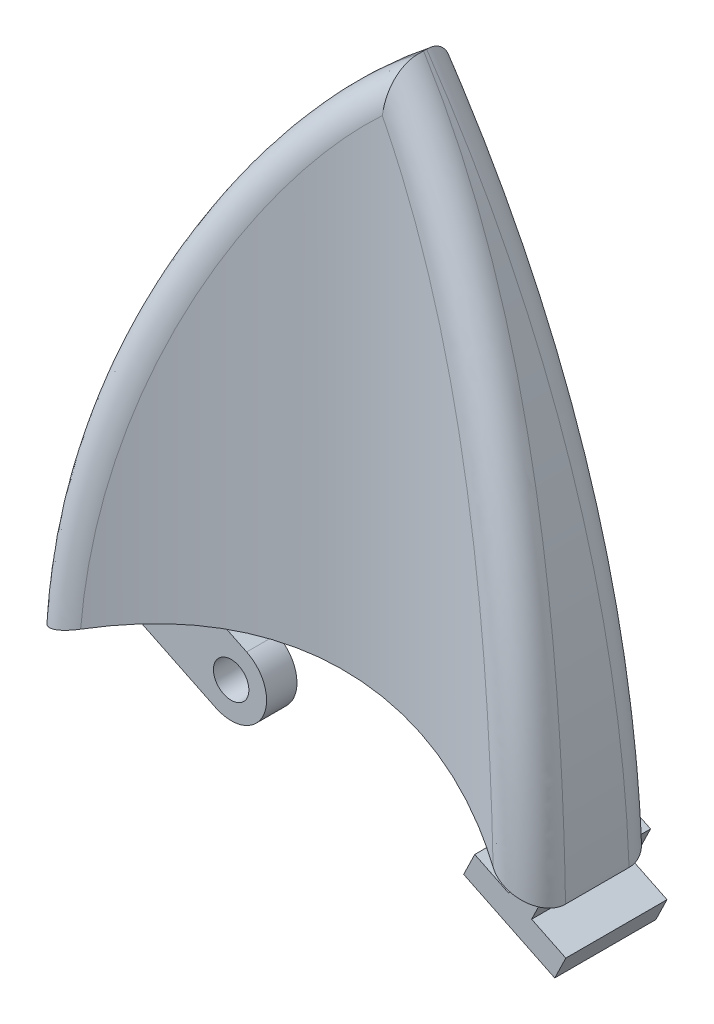
SolidWorks part; units mm, degrees
ref_plane "Plano frontal" through (0, 0, 0) normal (0, 0, 1) x (1, 0, 0)
ref_plane "Plano superior" through (0, 0, 0) normal (0, 1, 0) x (1, 0, 0)
ref_plane "Plano direito" through (0, 0, 0) normal (1, 0, 0) x (0, 0, -1)
sketch "Esboço6" plane through (0, 0, 0) normal (0, 0, 1) x (1, 0, 0)
  line L0 (0, 0) -> (0, 60.7591) construction
  line L1 (-45.3755, 22.0332) -> (30.2231, -14.6756) construction
  line L2 (20.4812, 42.1794) -> (-17.5967, -36.239) construction
  dimension "D1" = 64.1
sketch "Esboço1" plane through (0, 0, 0) normal (0, 1, 0) x (1, 0, 0)
  line L1 (-25, 0) -> (25, 0)
  line L2 (-25, 0) -> (-25, -15)
  line L3 (-25, -15) -> (25, -15)
  line L4 (25, 0) -> (25, -15)
  dimension "D2" = 15
  dimension "D1" = 50
extrude "Ressalto-extrusão1" add sketch "Esboço1" along normal blind 60
sketch "Esboço2" plane through (0, 0, 0) normal (0, 0, 1) x (1, 0, 0)
  line L1 (5, 60) -> (25, 60)
  line L2 (25, 60) -> (25, 0)
  line L4 (-25, 0) -> (25, 0) construction
  arc A0 (5, 60) -> (25, 0) centre (-88.2934, -4.4311) cw
  dimension "D1" = 20
  dimension "D2" = 113.38
extrude "Corte-extrusão1" cut sketch "Esboço2" along normal up to next and the other way through all
sketch "Esboço3" plane through (0, 0, 0) normal (0, 0, -1) x (-1, 0, 0)
  line L0 (-5, 60) -> (25, 60)
  line L1 (25, 60) -> (25, 0)
  line L2 (25, 0) -> (-25, 0) construction
  line L3 (25, 60) -> (25, 0) construction
  arc A0 (25, 0) -> (-5, 60) centre (-54.9615, -2.4808) ccw
  dimension "D1" = 80
extrude "Corte-extrusão2" cut sketch "Esboço3" against normal up to next
sketch "Esboço4" plane through (0, 0, 0) normal (0, -1, 0) x (1, 0, 0)
  line L0 (-25, 15) -> (25, 15) construction
  line L1 (-25, 0) -> (-25, 15) construction
  line L2 (-25, 15) -> (25, 15)
  arc A0 (-25, 15) -> (25, 15) centre (0, 46.225) ccw
  point P3 (0, 6.225)
  dimension "D1" = 40
extrude "Corte-extrusão3" cut sketch "Esboço4" against normal blind 60
fillet "Filete1" radius 3 4 edges at (19.2683, 31.4228, 0) (19.2315, 31.5331, 11.1515) (-16.5926, 33.2963, 0) (-12.5703, 40.408, 8.2515)
sketch "Esboço5" plane through (0, 0, 0) normal (0, 0, 1) x (1, 0, 0)
  line L0 (-25, 0) -> (25, 0)
  line L1 (20.4629, 0) -> (25, 0) construction
  arc A0 (-25, 0) -> (25, 0) centre (0, -48.9898) cw
  arc A1 (25, 0) -> (5, 60) centre (-88.2934, -4.4311) ccw construction
  dimension "D1" = 55
extrude "Corte-extrusão4" cut sketch "Esboço5" along normal up to next
sketch "Esboço7" plane through (0, 0, 0) normal (0, 0, -1) x (-1, 0, 0)
  line L0 (21.5017, -0.1085) -> (14.3052, -3.6029) construction
  line L1 (23.0305, -3.257) -> (15.834, -6.7514)
  line L2 (19.9729, 3.0399) -> (12.7764, -0.4545)
  line L4 (45.3755, 22.0332) -> (-30.2231, -14.6756) construction
  arc A0 (23.0305, -3.257) -> (19.9729, 3.0399) centre (21.5017, -0.1085) ccw
  arc A1 (12.7764, -0.4545) -> (15.834, -6.7514) centre (14.3052, -3.6029) ccw
  arc A3 (25, 0) -> (-4.9706, 59.9765) centre (-54.9615, -2.4808) ccw construction
  point P2 (17.9035, -1.8557)
  dimension "D1" = 7
  dimension "D2" = 8
extrude "Ressalto-extrusão2" add sketch "Esboço7" against normal blind 3
sketch "Esboço12" plane through (0, 0, 0) normal (0, 0, -1) x (-1, 0, 0)
  line L0 (-24.1209, 1.3571) -> (-22.3737, -2.2412)
  line L1 (-22.3737, -2.2412) -> (-25.747, -3.8792)
  line L2 (-25.747, -3.8792) -> (-24.655, -6.1281)
  line L3 (-24.655, -6.1281) -> (-15.6594, -1.76)
  line L4 (-15.6594, -1.76) -> (-16.7514, 0.4889)
  line L5 (-16.7514, 0.4889) -> (-20.1248, -1.1492)
  line L6 (-20.1248, -1.1492) -> (-21.872, 2.4491)
  line L7 (-21.872, 2.4491) -> (-24.1209, 1.3571)
  line L9 (45.3755, 22.0332) -> (-30.2231, -14.6756) construction
  arc A3 (-4.3614, 55.5591) -> (-21.9299, 1.4491) centre (88.2934, -4.4311) ccw construction
  dimension "D1" = 2.5
  dimension "D2" = 4
  dimension "D3" = 10
  dimension "D4" = 1
extrude "Ressalto-extrusão5" add sketch "Esboço12" against normal blind 10
sketch "Esboço13" plane through (0, 0, 0) normal (0, 0, -1) x (-1, 0, 0)
  circle A0 centre (14.3052, -3.6029) radius 1.75
  arc A1 (12.7764, -0.4545) -> (15.834, -6.7514) centre (14.3052, -3.6029) ccw construction
  dimension "D1" = 3.5
extrude "Corte-extrusão5" cut sketch "Esboço13" against normal up to next
